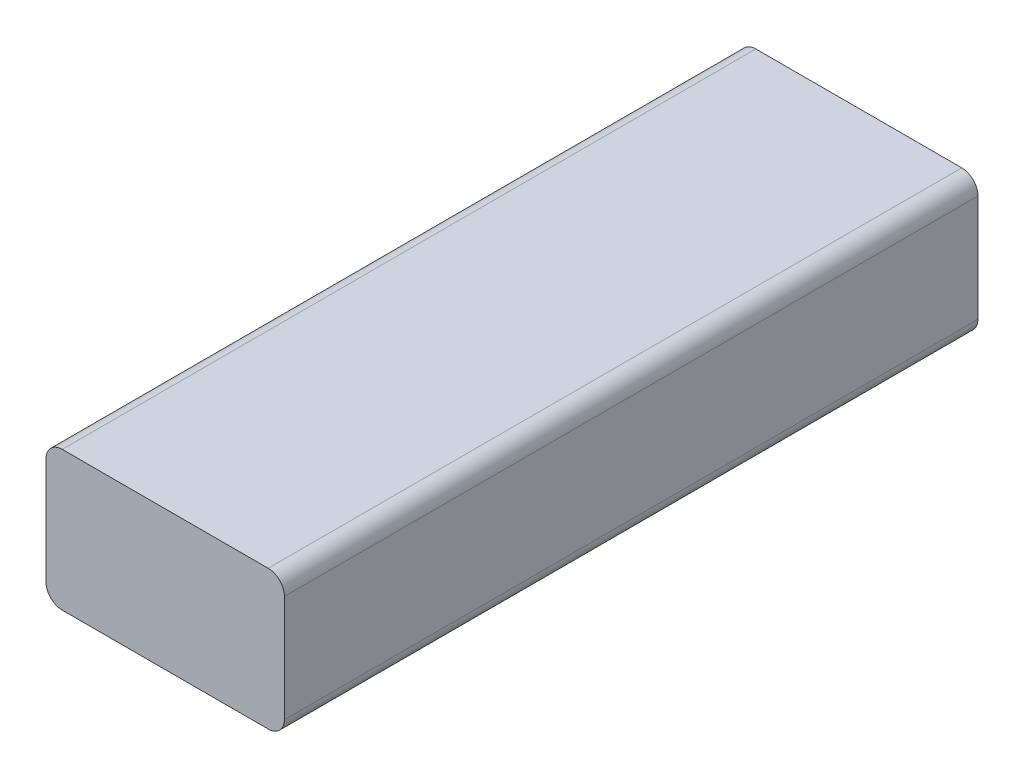
SolidWorks part; units mm, degrees
ref_plane "Front Plane" through (0, 0, 0) normal (0, 0, 1) x (1, 0, 0)
ref_plane "Top Plane" through (0, 0, 0) normal (0, 1, 0) x (1, 0, 0)
ref_plane "Right Plane" through (0, 0, 0) normal (1, 0, 0) x (0, 0, -1)
sketch "Sketch2" plane through (0, 0, 0) normal (0, 0, 1) x (1, 0, 0)
  line L1 (-19, -12.85) -> (19, -12.85)
  line L2 (-22, -9.85) -> (-22, 9.85)
  line L3 (-19, 12.85) -> (19, 12.85)
  line L4 (22, -9.85) -> (22, 9.85)
  line L5 (-22, -12.85) -> (22, 12.85) construction
  line L6 (-22, 12.85) -> (22, -12.85) construction
  arc A0 (-22, -9.85) -> (-19, -12.85) centre (-19, -9.85) ccw
  arc A1 (19, -12.85) -> (22, -9.85) centre (19, -9.85) ccw
  arc A2 (22, 9.85) -> (19, 12.85) centre (19, 9.85) ccw
  arc A3 (-22, 9.85) -> (-19, 12.85) centre (-19, 9.85) cw
  point P0 (0, 0)
  dimension "D3" = 3
  dimension "D1" = 25.7
  dimension "D2" = 44
extrude "Boss-Extrude1" add sketch "Sketch2" along normal mid plane 128
